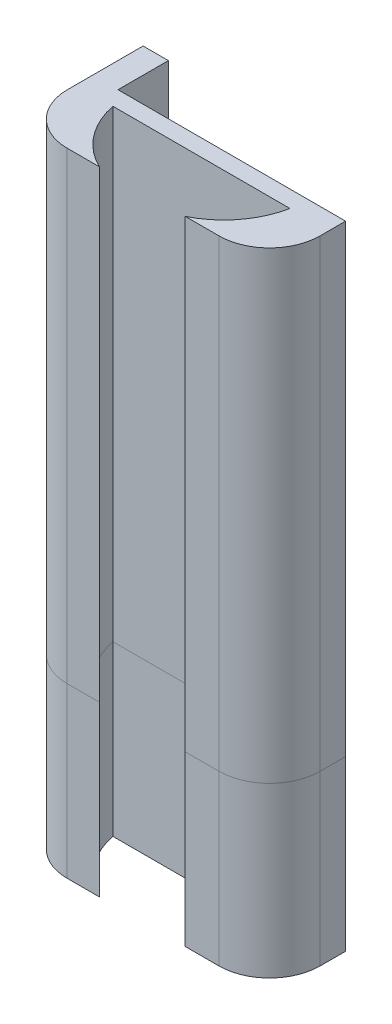
SolidWorks part; units mm, degrees
ref_plane "Front Plane" through (0, 0, 0) normal (1, 0, 0) x (0, 1, 0)
ref_plane "Top Plane" through (0, 0, 0) normal (0, 0, 1) x (0, 1, 0)
ref_plane "Right Plane" through (0, 0, 0) normal (0, 1, 0) x (-1, 0, 0)
sketch "Sketch1" plane through (0, 0, 0) normal (0, 0, 1) x (0, 1, 0)
  line L1 (-37.5, -15) -> (37.5, -15)
  line L2 (-37.5, -15) -> (-37.5, 15)
  line L3 (-37.5, 15) -> (37.5, 15)
  line L4 (37.5, -15) -> (37.5, 15)
  line L5 (-37.5, -15) -> (37.5, 15) construction
  line L6 (-37.5, 15) -> (37.5, -15) construction
  point P0 (0, 0)
  dimension "D1" = 30
  dimension "D2" = 75
extrude "Boss-Extrude1" add sketch "Sketch1" along normal blind 15 contours L3 L4 L1 L2
sketch "Sketch2" plane through (0, 37.5, 0) normal (0, 1, 0) x (-1, 0, 0)
  line L1 (-5, 7.98) -> (5.2, 7.98)
  line L2 (-5, 7.98) -> (-5, 15)
  line L3 (-5, 15) -> (5.2, 15)
  line L4 (5.2, 7.98) -> (5.2, 15)
  line L6 (-15, 15) -> (-15, 0) construction
  line L7 (-15, 15) -> (15, 15) construction
  line L8 (-5, 7.98) -> (-10.4, 7.98)
  line L9 (5.2, 7.98) -> (10.6, 7.98)
  line L10 (-15, 0) -> (15, 0) construction
  line L11 (-12, 0) -> (12, 0)
  line L12 (-12, 0) -> (-12, 5.98)
  line L13 (-12, 5.98) -> (12, 5.98)
  line L14 (12, 0) -> (12, 5.98)
  line L15 (15, 15) -> (15, 0) construction
  arc A0 (-10.4, 7.98) -> (-5, 15) centre (-0.5933, 6.0233) cw
  arc A1 (5.2, 15) -> (10.6, 7.98) centre (0.7933, 6.0233) cw
  line M9 (15, 15) -> (-15, 15)
  dimension "D7" = 10
  dimension "D8" = 10
  dimension "D1" = 10.2
  dimension "D2" = 10
  dimension "D3" = 7.02
  dimension "D4" = 0
  dimension "D5" = 5.4
  dimension "D6" = 5.4
  dimension "D9" = 3
  dimension "D10" = 3
  dimension "D11" = 2
extrude "Cut-Extrude1" cut sketch "Sketch2" against normal through all contours A0 L8 L2 | L1 L4 L2 M9 | A1 L4 L9 | L12 L11 L14 L13
sketch "Sketch3" plane through (15, 0, 0) normal (1, 0, 0) x (0, 1, 0)
  line L0 (-40, 2.5) -> (-22.5, 2.5) construction
  line L1 (2.4331, 2.5) -> (0.862, 3.8354)
  line L2 (-20.0013, 2.5) -> (-21.25, 1.5013)
  line L3 (-37.5, 0) -> (37.5, 0) construction
  line L4 (-37.5, 15) -> (-37.5, 0) construction
  line L5 (0, 0) -> (0, 10.3697) construction
  line L6 (-20.0013, 2.5) -> (-21.25, 3.4988)
  line L7 (-20.0013, 2.5) -> (1.5765, 2.5) construction
  line L8 (2.4331, 2.5) -> (0.8452, 1.1845)
  line L9 (2.4331, 2.5) -> (40, 2.5) construction
  line L10 (20.0013, 2.5) -> (21.25, 1.5013)
  line L11 (20.0013, 2.5) -> (21.25, 3.4988)
  arc A0 (-21.25, 3.4988) -> (-21.25, 1.5013) centre (-22.5, 2.5) ccw
  arc A1 (0.862, 3.8354) -> (0.8452, 1.1845) centre (0, 2.5153) ccw
  arc A3 (21.25, 3.4988) -> (21.25, 1.5013) centre (22.5, 2.5) cw
  dimension "D1" = 3.2
  dimension "D4" = 15
  dimension "D5" = 1.599
  dimension "D3" = 1.6
  dimension "D2" = 2.5
  dimension "D6" = 1.599
  dimension "D7" = 2.062
  dimension "D8" = 1.9975
extrude "Cut-Extrude2" cut sketch "Sketch3" against normal through all
sketch "Sketch4" plane through (0, 0, 0) normal (0, 0, -1) x (1, 0, 0)
  line L0 (-15, 17.5) -> (15, 17.5)
  line L1 (12, 37.5) -> (-12, 37.5) construction
  dimension "D1" = 20
fillet "Fillet2" radius 6 2 edges at (-15, 0, 15) (15, 0, 15)
sketch "Sketch5" plane through (0, -37.5, 0) normal (0, -1, 0) x (1, 0, 0)
  line L1 (12, 5.98) -> (15, 5.98)
  line L2 (12, 5.98) -> (12, 0)
  line L3 (12, 0) -> (15, 0)
  line L4 (15, 5.98) -> (15, 0)
extrude "Cut-Extrude3" cut sketch "Sketch5" against normal through all
split "Split1" trim tools "Sketch4" bodies to split 106 resulting bodies 104 105
